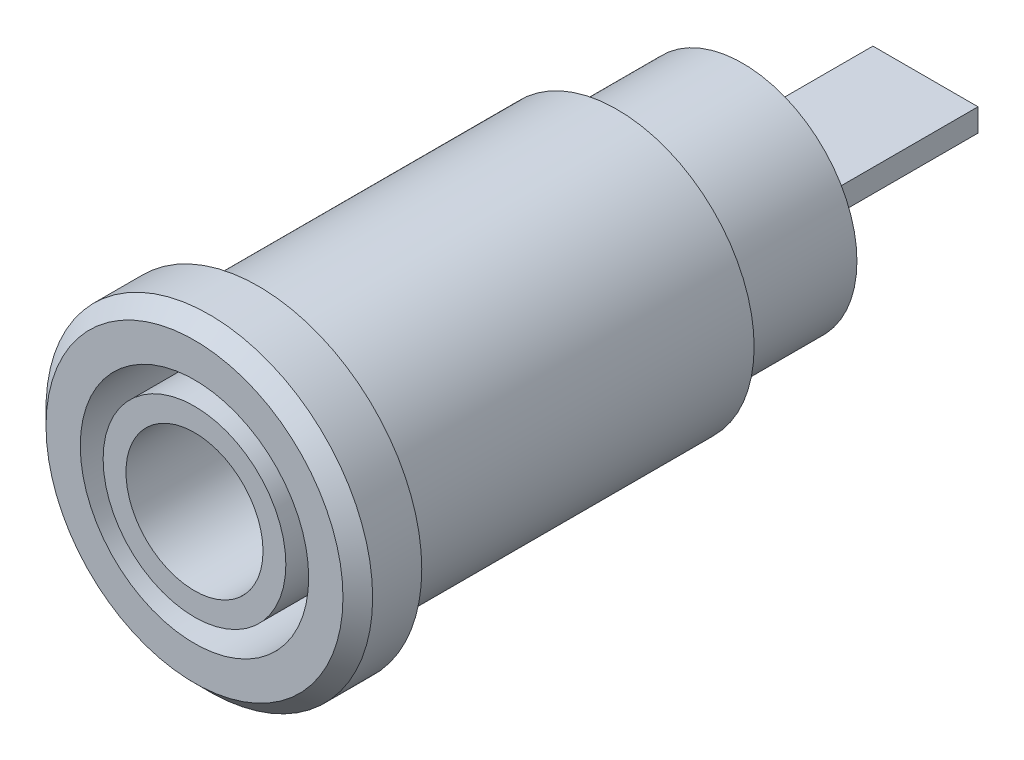
SolidWorks part; units mm, degrees
ref_plane "Piano frontale" through (0, 0, 0) normal (0, 0, 1) x (1, 0, 0)
ref_plane "Piano superiore" through (0, 0, 0) normal (0, 1, 0) x (1, 0, 0)
ref_plane "Piano destro" through (0, 0, 0) normal (1, 0, 0) x (0, 0, -1)
sketch "Schizzo1" plane through (0, 0, 0) normal (1, 0, 0) x (0, 0, -1)
  line L2 (-17, 6.5) -> (-16.35, 7.15)
  line L3 (-16.35, 7.15) -> (-14.2, 7.15)
  line L4 (-14.2, 7.15) -> (-14.2, 6)
  line L5 (-14.2, 6) -> (1.5, 6)
  line L6 (1.5, 6) -> (2, 5)
  line L7 (2, 5) -> (7, 5)
  line L8 (7, 5) -> (7, 0)
  line L9 (-17, 5) -> (0, 5)
  line L10 (0, 5) -> (0, 4)
  line L11 (0, 4) -> (-17, 4)
  line L12 (-17, 4) -> (-17, 3)
  line L13 (-17, 3) -> (0, 3)
  line L14 (0, 3) -> (0, 0)
  line L15 (-17, 5) -> (-17, 6.5)
  line L16 (0, 0) -> (7, 0)
  dimension "D1" = 1
  dimension "D2" = 21.2
  dimension "D3" = 1
  dimension "D4" = 135
  dimension "D5" = 5
  dimension "D6" = 0.5
  dimension "D7" = 5
  dimension "D8" = 1.5
  dimension "D9" = 17
  dimension "D10" = 1
  dimension "D11" = 7
  dimension "D12" = 2.15
revolve "Rivoluzione1" add sketch "Schizzo1" angle 360 about L16
sketch "Schizzo2" plane through (0, 0, -7) normal (0, 0, -1) x (-1, 0, 0)
  line L1 (-2.3, -0.5) -> (2.3, -0.5)
  line L2 (-2.3, -0.5) -> (-2.3, 0.5)
  line L3 (-2.3, 0.5) -> (2.3, 0.5)
  line L4 (2.3, -0.5) -> (2.3, 0.5)
  line L5 (-2.3, -0.5) -> (2.3, 0.5) construction
  line L6 (-2.3, 0.5) -> (2.3, -0.5) construction
  point P0 (0, 0)
  dimension "D1" = 1
  dimension "D2" = 4.6
extrude "Estrusione-Estrusione1" add sketch "Schizzo2" along normal blind 8
